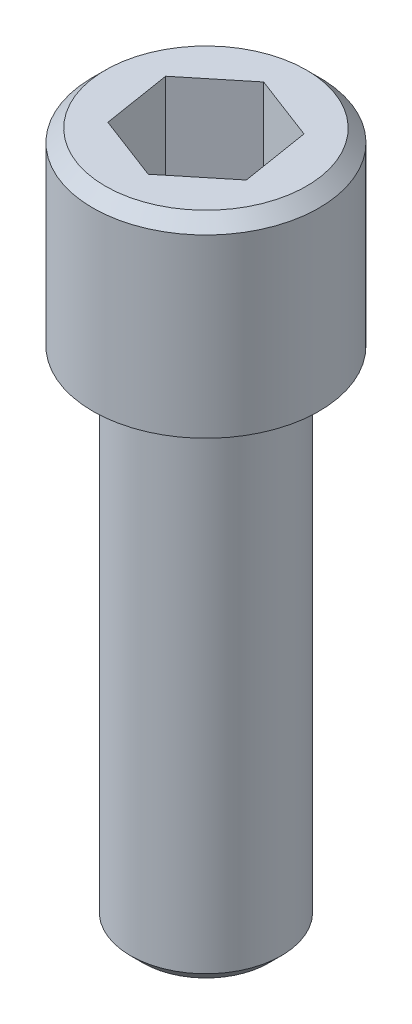
SolidWorks part; units mm, degrees
ref_plane "Přední rovina" through (0, 0, 0) normal (0, 0, 1) x (1, 0, 0)
ref_plane "Horní rovina" through (0, 0, 0) normal (0, 1, 0) x (1, 0, 0)
ref_plane "Pravá rovina" through (0, 0, 0) normal (1, 0, 0) x (0, 0, -1)
sketch "Skica1" plane through (0, 0, 0) normal (0, 1, 0) x (1, 0, 0)
  circle A0 centre (0, 0) radius 1.5
  dimension "D1" = 3
extrude "Přidat vysunutím1" add sketch "Skica1" along normal blind 10
sketch "Skica2" plane through (0, 10, 0) normal (0, 1, 0) x (1, 0, 0)
  circle A0 centre (0, 0) radius 2.25
  dimension "D1" = 4.5
extrude "Přidat vysunutím2" add sketch "Skica2" along normal blind 3.75
sketch "Skica3" plane through (0, 13.75, 0) normal (0, 1, 0) x (1, 0, 0)
  line L1 (-1.0744, -0.875) -> (0.2206, -1.368)
  line L2 (0.2206, -1.368) -> (1.295, -0.493)
  line L3 (1.295, -0.493) -> (1.0744, 0.875)
  line L4 (1.0744, 0.875) -> (-0.2206, 1.368)
  line L5 (-0.2206, 1.368) -> (-1.295, 0.493)
  line L6 (-1.295, 0.493) -> (-1.0744, -0.875)
  circle A0 centre (0, 0) radius 1.2 construction
  dimension "D1" = 2.4
extrude "Odebrat vysunutím1" cut sketch "Skica3" against normal blind 2.25
chamfer "Zkosení1" distance 0.25 angle 45 1 edges at (0, 13.75, 2.25)
chamfer "Zkosení2" distance 0.25 angle 45 1 edges at (0, 0, 1.5)
